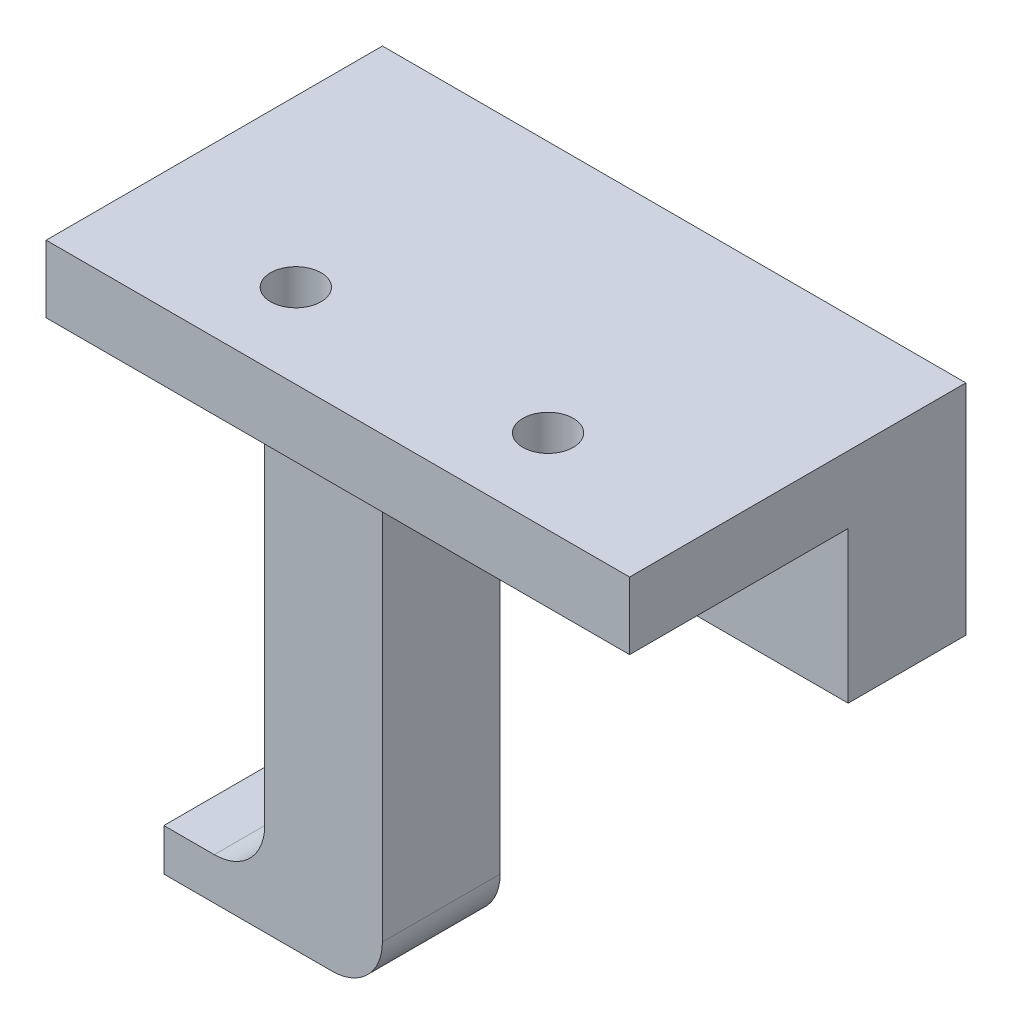
SolidWorks part; units mm, degrees
ref_plane "Front Plane" through (0, 0, 0) normal (0, 0, 1) x (1, 0, 0)
ref_plane "Top Plane" through (0, 0, 0) normal (0, 1, 0) x (1, 0, 0)
ref_plane "Right Plane" through (0, 0, 0) normal (1, 0, 0) x (0, 0, -1)
sketch "Sketch1" plane through (0, 0, 0) normal (0, 0, 1) x (1, 0, 0)
  line L0 (0, -26.65) -> (0, -29.15) construction
  line L1 (7, 0) -> (34.7, 0)
  line L2 (0, 0) -> (0, 9)
  line L3 (0, 9) -> (34.7, 9)
  line L4 (34.7, 0) -> (34.7, 9)
  line L6 (0, 0) -> (0, -26.65)
  line L7 (0, -29.15) -> (7, -29.15)
  line L8 (7, 0) -> (7, -29.15)
  line L9 (0, -29.15) -> (-6, -29.15)
  line L11 (0, -26.65) -> (-6, -26.65)
  line L12 (-6, -29.15) -> (-6, -26.65)
  line L13 (0, 0) -> (7, 0) construction
  dimension "D1" = 9
  dimension "D2" = 34.7
  dimension "D3" = 7
  dimension "D4" = 38.15
  dimension "D6" = 2.5
  dimension "D7" = 6
extrude "Boss-Extrude1" add sketch "Sketch1" along normal blind 7
fillet "Fillet1" radius 3 3 edges at (7, 0, 3.5) (7, -29.15, 3.5) (0, -26.65, 3.5)
sketch "Sketch3" plane through (0, 9, 0) normal (0, 1, 0) x (1, 0, 0)
  line L0 (0, -7) -> (0, 0) construction
  line L1 (34.7, 0) -> (0, 0)
  line L2 (34.7, 0) -> (34.7, -20)
  line L3 (34.7, -20) -> (0, -20)
  line L4 (0, 0) -> (0, -20)
  line L16 (24.85, -15) -> (9.85, -15) construction
  circle A0 centre (24.85, -15) radius 1.5
  circle A1 centre (9.85, -15) radius 1.5
  dimension "D2" = 3
  dimension "D3" = 5
  dimension "D4" = 9.85
  dimension "D5" = 5
  dimension "D1" = 20
  dimension "D6" = 15
extrude "Boss-Extrude2" add sketch "Sketch3" along normal blind 4
